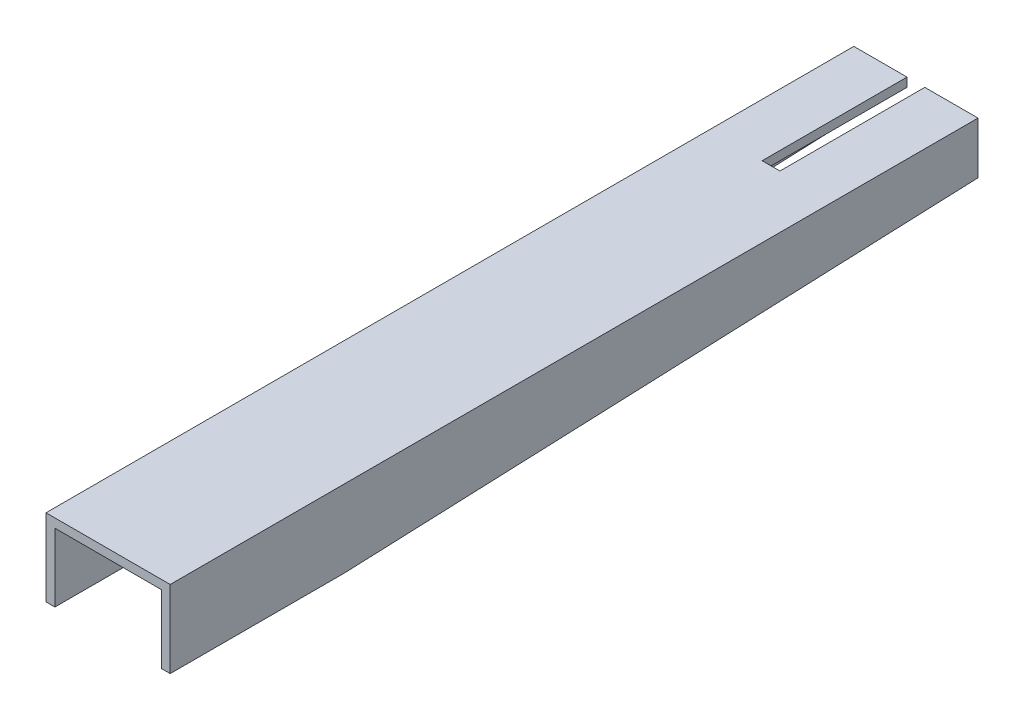
SolidWorks part; units mm, degrees
ref_plane "Front Plane" through (0, 0, 0) normal (0, 0, 1) x (1, 0, 0)
ref_plane "Top Plane" through (0, 0, 0) normal (0, 1, 0) x (1, 0, 0)
ref_plane "Right Plane" through (0, 0, 0) normal (1, 0, 0) x (0, 0, -1)
sketch "Sketch1" plane through (0, 0, 0) normal (0, 0, 1) x (1, 0, 0)
  line L0 (-30, 0) -> (-25.7, 0)
  line L5 (-25.7, 0) -> (-25.7, 20.7)
  line L6 (-25.7, 20.7) -> (25.7, 20.7)
  line L7 (25.7, 20.7) -> (25.7, 0)
  line L8 (25.7, 0) -> (30, 0)
  line L9 (30, 0) -> (30, 25)
  line L10 (30, 25) -> (-30, 25)
  line L11 (-30, 25) -> (-30, 0)
  point P9 (0, 20.7)
  dimension "D1" = 4.3
  dimension "D2" = 4.3
  dimension "D3" = 60
  dimension "D4" = 25
extrude "Boss-Extrude1" add sketch "Sketch1" along normal blind 390.3
sketch "Sketch2" plane through (30, 0, 0) normal (1, 0, 0) x (0, 0, -1)
  line L0 (-306, 0) -> (-306, -12.31) construction
  line L1 (-306, -12.31) -> (0, 0)
  line L2 (0, 0) -> (-390.3, 0)
  line L3 (-390.3, 0) -> (-390.3, -12.31)
  line L4 (-390.3, -12.31) -> (-306, -12.31)
  point P6 (-283.4232, -12.31)
  point P9 (-306, 0)
  dimension "D1" = 306
  dimension "D2" = 12.31
extrude "Boss-Extrude2" add sketch "Sketch2" against normal blind 4.3
mirror "Mirror1" about plane through (0, 0, 0) normal (1, 0, 0) of "Boss-Extrude2"
sketch "Sketch3" plane through (0, 25, 0) normal (0, 1, 0) x (1, 0, 0)
  line L0 (-20.5205, 0) -> (20.5205, 0) construction
  line L1 (-4.3, 0) -> (4.3, 0)
  line L2 (-4.3, 0) -> (-4.3, -70)
  line L3 (-4.3, -70) -> (4.3, -70)
  line L4 (4.3, 0) -> (4.3, -70)
  line L5 (0, -20.5205) -> (0, 20.5205) construction
  point P6 (0, 0)
  dimension "D1" = 70
  dimension "D2" = 8.6
extrude "Cut-Extrude1" cut sketch "Sketch3" against normal blind 10
